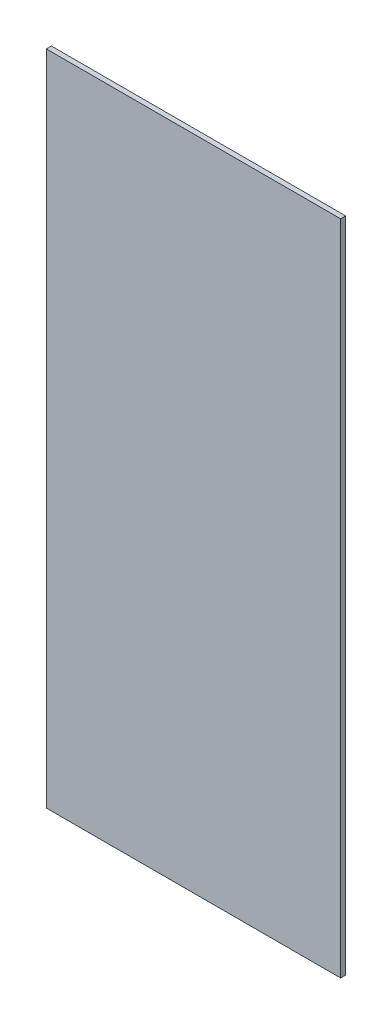
SolidWorks part; units mm, degrees
ref_plane "Front Plane" through (0, 0, 0) normal (0, 0, 1) x (1, 0, 0)
ref_plane "Top Plane" through (0, 0, 0) normal (0, 1, 0) x (1, 0, 0)
ref_plane "Right Plane" through (0, 0, 0) normal (1, 0, 0) x (0, 0, -1)
sketch "Sketch1" plane through (0, 0, 0) normal (0, 0, 1) x (1, 0, 0)
  line L0 (0, -262.5) -> (0, 0) construction
  line L1 (-117.5, 262.5) -> (117.5, 262.5)
  line L2 (-117.5, 262.5) -> (-117.5, -262.5)
  line L3 (-117.5, -262.5) -> (117.5, -262.5)
  line L4 (117.5, 262.5) -> (117.5, -262.5)
  line L5 (0, 0) -> (0, 262.5) construction
  dimension "D1" = 525
  dimension "D2" = 235
extrude "Boss-Extrude1" add sketch "Sketch1" along normal blind 4
